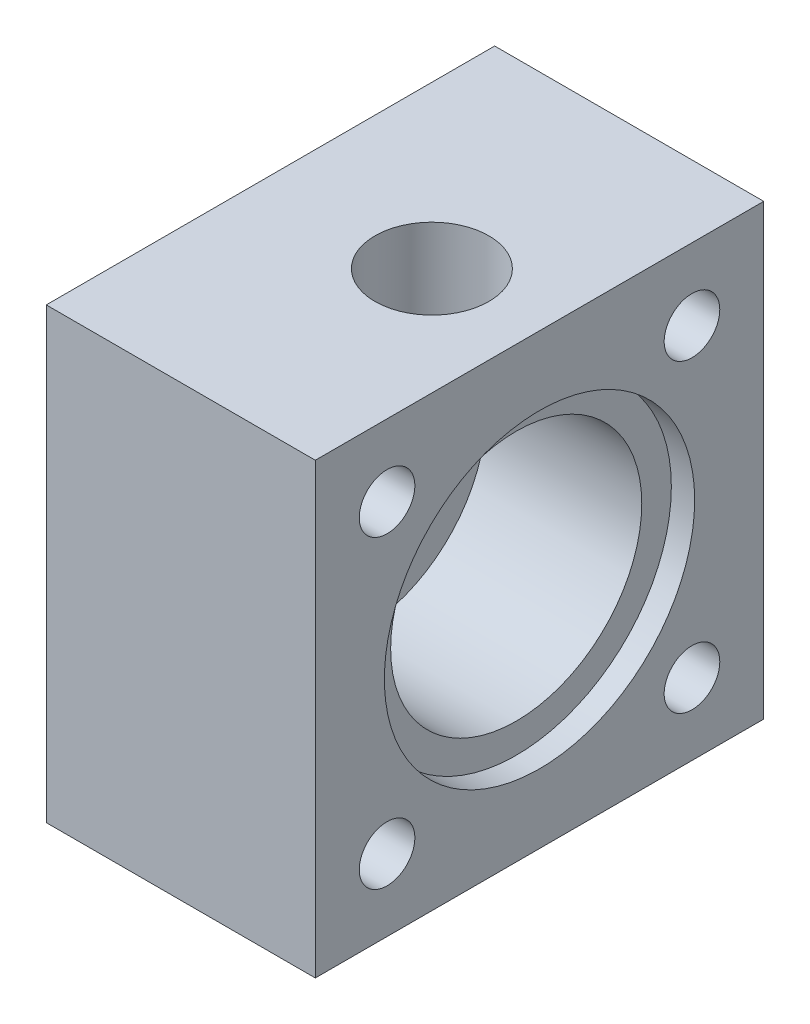
SolidWorks part; units mm, degrees
ref_plane "Front Plane" through (0, 0, 0) normal (0, 0, 1) x (1, 0, 0)
ref_plane "Top Plane" through (0, 0, 0) normal (0, 1, 0) x (1, 0, 0)
ref_plane "Right Plane" through (0, 0, 0) normal (1, 0, 0) x (0, 0, -1)
sketch "Sketch1" plane through (0, 0, 0) normal (1, 0, 0) x (0, 0, -1)
  line L1 (0, 0) -> (25, 0)
  line L2 (0, 0) -> (0, 25)
  line L3 (0, 25) -> (25, 25)
  line L4 (25, 0) -> (25, 25)
  circle A0 centre (4, 4) radius 1.55
  circle A1 centre (4, 21) radius 1.55
  circle A2 centre (21, 21) radius 1.55
  circle A3 centre (21, 4) radius 1.55
extrude "Extrude1" add sketch "Sketch1" against normal blind 15
sketch "Sketch2" plane through (0, 0, 0) normal (1, 0, 0) x (0, 0, -1)
  circle A0 centre (12.5, 12.5) radius 7
extrude "Cut-Extrude1" cut sketch "Sketch2" against normal offset from surface (10 mm away) 5 up to face at (-15, 4, -22.55)
sketch "Sketch3" plane through (0, 0, 0) normal (1, 0, 0) x (0, 0, -1)
  circle A0 centre (12.5, 12.5) radius 3.175
extrude "Cut-Extrude2" cut sketch "Sketch3" against normal through all
sketch "Sketch4" plane through (0, 25, 0) normal (0, 1, 0) x (1, 0, 0)
  circle A0 centre (-6, 12.5) radius 3.175
extrude "Cut-Extrude3" cut sketch "Sketch4" against normal blind 10
sketch "Sketch7" plane through (0, 0, 0) normal (1, 0, 0) x (0, 0, -1)
  circle A0 centre (12.5, 12.5) radius 8.65
extrude "Cut-Extrude4" cut sketch "Sketch7" against normal blind 1.3
